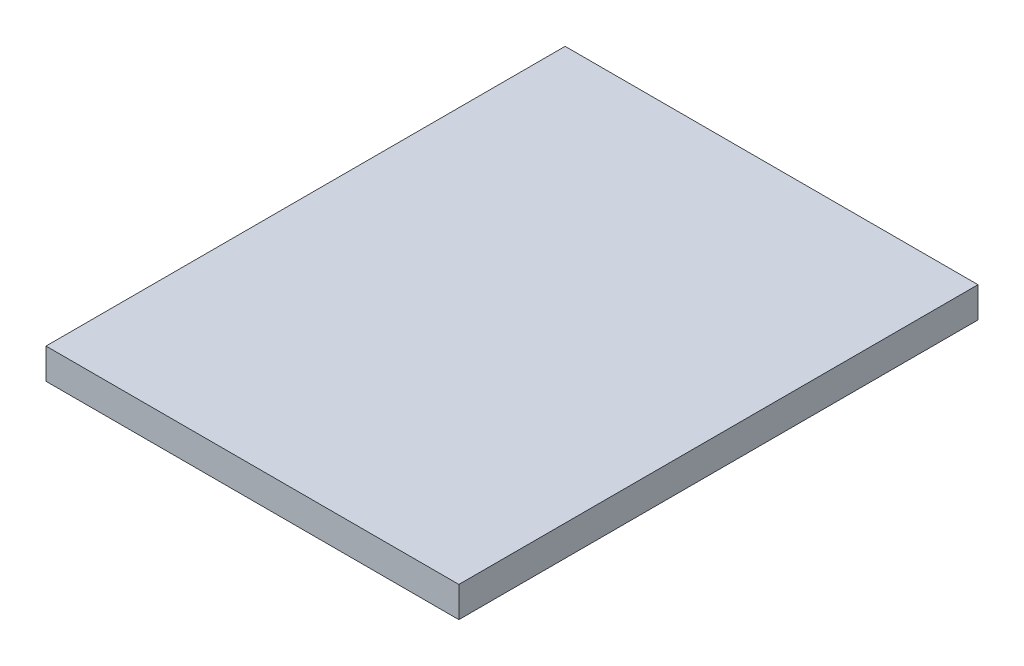
SolidWorks part; units mm, degrees
ref_plane "Front Plane" through (0, 0, 0) normal (0, 0, 1) x (1, 0, 0)
ref_plane "Top Plane" through (0, 0, 0) normal (0, 1, 0) x (1, 0, 0)
ref_plane "Right Plane" through (0, 0, 0) normal (1, 0, 0) x (0, 0, -1)
sketch "Sketch1" plane through (0, 0, 0) normal (0, 1, 0) x (1, 0, 0)
  line L1 (-42.926, 53.975) -> (42.926, 53.975)
  line L2 (-42.926, 53.975) -> (-42.926, -53.975)
  line L3 (-42.926, -53.975) -> (42.926, -53.975)
  line L4 (42.926, 53.975) -> (42.926, -53.975)
  line L5 (-42.926, 53.975) -> (42.926, -53.975) construction
  line L6 (-42.926, -53.975) -> (42.926, 53.975) construction
  point P0 (0, 0)
  dimension "D1" = 85.852
  dimension "D2" = 107.95
extrude "Boss-Extrude1" add sketch "Sketch1" along normal blind 6.35
